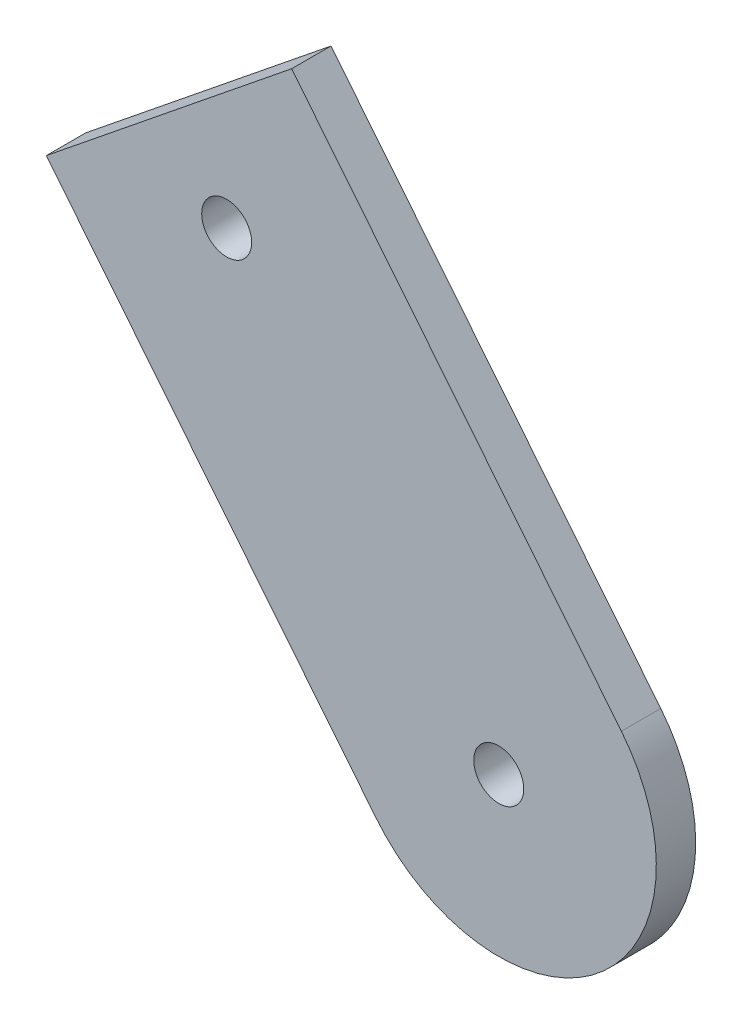
SolidWorks part; units mm, degrees
ref_plane "Plan de face" through (0, 0, 0) normal (0, 0, 1) x (1, 0, 0)
ref_plane "Plan de dessus" through (0, 0, 0) normal (0, 1, 0) x (1, 0, 0)
ref_plane "Plan de droite" through (0, 0, 0) normal (1, 0, 0) x (0, 0, -1)
sketch "Esquisse1" plane through (0, 0, 48.781) normal (0, 0, -1) x (-1, 0, 0)
  line L0 (-139.9908, 150.7435) -> (-227.8896, 41.7765) construction
  line L1 (-246.5696, 56.8449) -> (-221.4557, 87.9783)
  line L2 (-246.5696, 56.8449) -> (-158.6709, 165.8119) construction
  line L3 (-221.4557, 87.9783) -> (-202.7756, 72.9099)
  line L4 (-202.7756, 72.9099) -> (-227.8896, 41.7765)
  line L5 (-237.2296, 49.3107) -> (-212.1157, 80.4441) construction
  arc A0 (-246.5696, 56.8449) -> (-227.8896, 41.7765) centre (-237.2296, 49.3107) ccw
  arc A1 (-246.5696, 56.8449) -> (-227.8896, 41.7765) centre (-237.2296, 49.3107) ccw construction
  circle A2 centre (-237.2296, 49.3107) radius 1.9024
  circle A3 centre (-216.5106, 74.9958) radius 1.9024
  circle A4 centre (-188.8853, 109.2425) radius 1.9024 construction
  dimension "D1" = 7
  dimension "D2" = 33
extrude "Boss.-Extru.1" add sketch "Esquisse1" along normal blind 3
